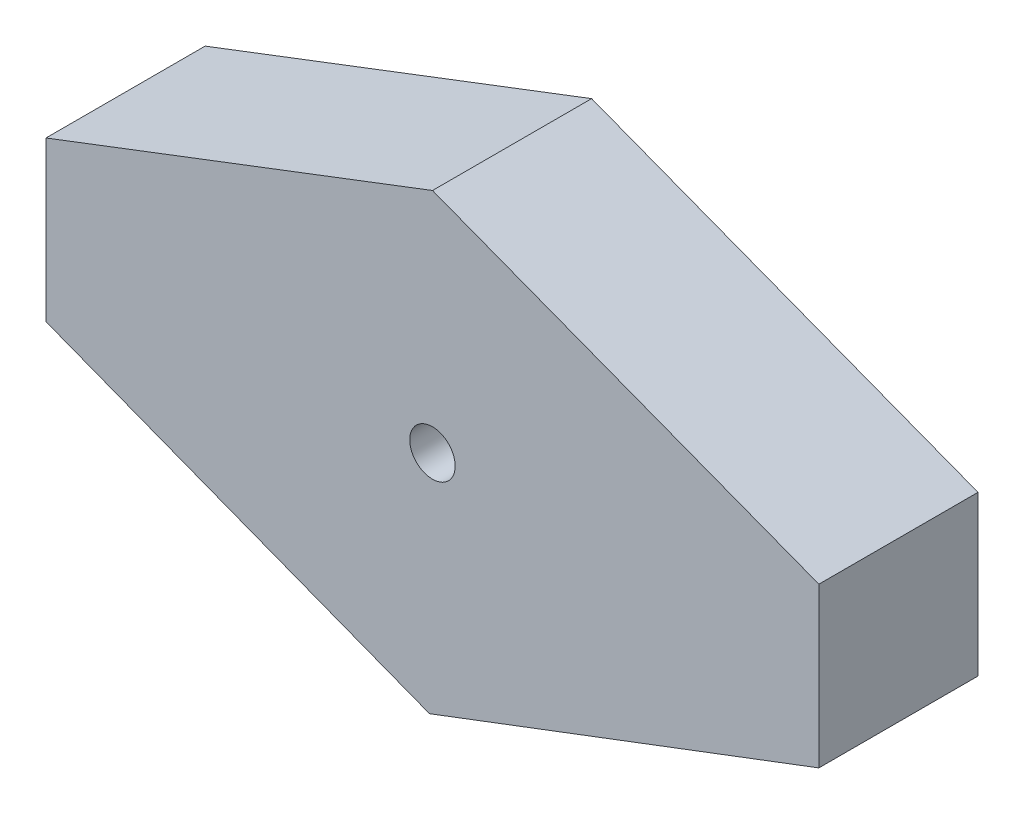
SolidWorks part; units mm, degrees
material "Bleibronze"
ref_plane "Ebene vorne" through (0, 0, 0) normal (0, 0, 1) x (1, 0, 0)
ref_plane "Ebene oben" through (0, 0, 0) normal (0, 1, 0) x (1, 0, 0)
ref_plane "Ebene rechts" through (0, 0, 0) normal (1, 0, 0) x (0, 0, -1)
sketch "Skizze1" plane through (0, 0, 0) normal (0, 0, 1) x (1, 0, 0)
  line L0 (0, 0) -> (0, -1)
  line L1 (-0.1293, -9.9992) -> (-17, -3.5)
  line L2 (-17, -3.5) -> (-17, 3.5)
  line L3 (-17, 3.5) -> (0.0033, 10.0004)
  line L4 (0, 0) -> (-36.15, 0) construction
  line L5 (17, -3.5) -> (17, 3.5)
  line L6 (-0.1293, -9.9992) -> (17, -3.5)
  line L7 (17, 3.5) -> (0.0033, 10.0004)
  circle A0 centre (0, 0) radius 1
  point P7 (-17, 0)
  point P12 (0, -10.3129)
  point P13 (0, 9.7469)
  dimension "D3" = 2
  dimension "D1" = 20
  dimension "D2" = 7
  dimension "D4" = 17
  dimension "D5" = 10
extrude "Aufsatz-Linear austragen1" add sketch "Skizze1" along normal blind 7
